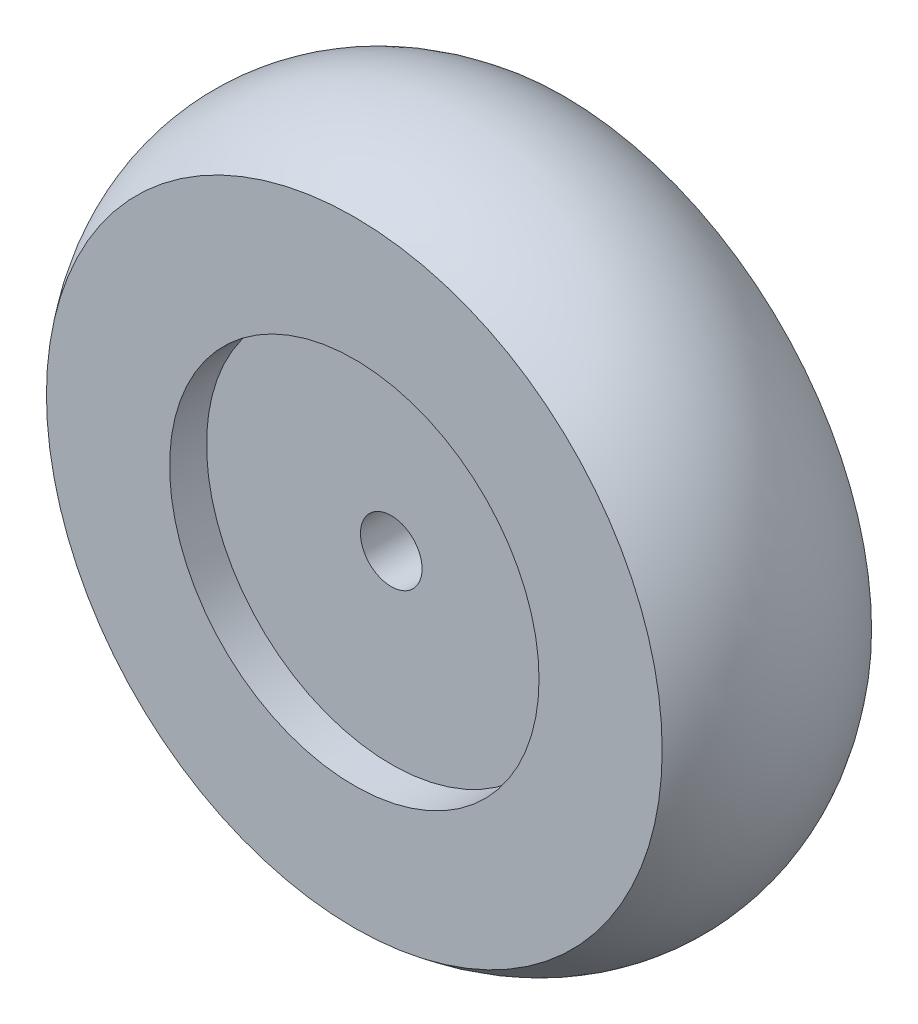
SolidWorks part; units mm, degrees
ref_plane "前视基准面" through (0, 0, 0) normal (0, 0, 1) x (1, 0, 0)
ref_plane "上视基准面" through (0, 0, 0) normal (0, 1, 0) x (1, 0, 0)
ref_plane "右视基准面" through (0, 0, 0) normal (1, 0, 0) x (0, 0, -1)
sketch "草图1" plane through (0, 0, 0) normal (0, 0, 1) x (1, 0, 0)
  circle A0 centre (0, 0) radius 25
  dimension "D1" = 50
extrude "凸台-拉伸1" add sketch "草图1" along normal blind 17
sketch "草图3" plane through (0, 0, 0) normal (0, 1, 0) x (1, 0, 0)
  line L0 (25, 0) -> (-25, 0) construction
  line L1 (25, -17) -> (25, 0) construction
  line L2 (25, -17) -> (25, 0)
  arc A0 (25, 0) -> (25, -17) centre (14.6324, -8.5) cw
sweep "扫描1" add profiles "草图3" path edge at (25, 0, 17)
sketch "草图4" plane through (0, 0, 0) normal (0, 0, -1) x (-1, 0, 0)
  circle A0 centre (0, 0) radius 15
extrude "切除-拉伸1" cut sketch "草图4" against normal blind 3
sketch "草图5" plane through (0, 0, 17) normal (0, 0, 1) x (1, 0, 0)
  circle A1 centre (0, 0) radius 15
  circle A2 centre (0, 0) radius 15
  dimension "D1" = 0
extrude "切除-拉伸2" cut sketch "草图5" against normal blind 3
sketch "草图6" plane through (0, 0, 3) normal (0, 0, -1) x (-1, 0, 0)
  circle A0 centre (0, 0) radius 2.5
  dimension "D1" = 5
extrude "切除-拉伸3" cut sketch "草图6" against normal up to next
